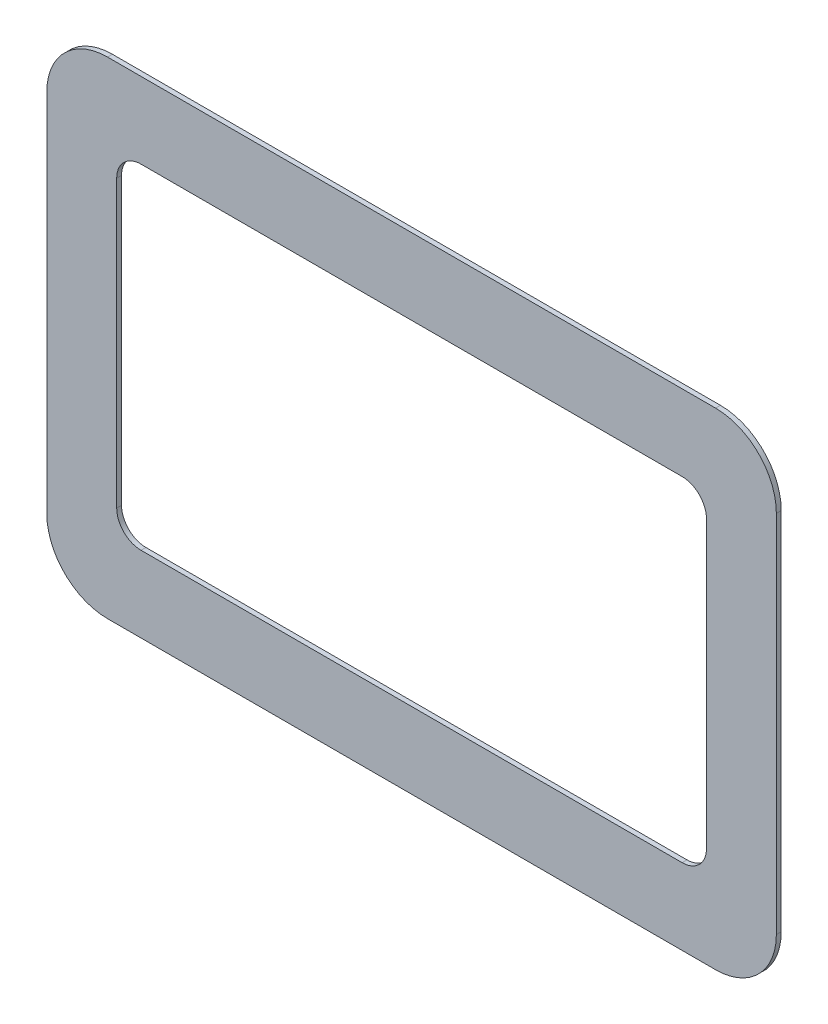
SolidWorks part; units mm, degrees
material "ABS"
ref_plane "Front Plane" through (0, 0, 0) normal (0, 0, 1) x (1, 0, 0)
ref_plane "Top Plane" through (0, 0, 0) normal (0, 1, 0) x (1, 0, 0)
ref_plane "Right Plane" through (0, 0, 0) normal (1, 0, 0) x (0, 0, -1)
sketch "Sketch1" plane through (0, 0, 0) normal (0, 0, 1) x (1, 0, 0)
  line L0 (-151.096, 0) -> (165.8124, 0) construction
  line L1 (0, -100.7307) -> (0, 98.9546) construction
  line L3 (-210.2936, -194.6079) -> (289.7064, -194.6079)
  line L4 (-260.2936, -144.6079) -> (-260.2936, 155.3921)
  line L5 (-210.2936, 205.3921) -> (289.7064, 205.3921)
  line L6 (339.7064, -144.6079) -> (339.7064, 155.3921)
  line L7 (-260.2936, -194.6079) -> (339.7064, 205.3921) construction
  line L8 (-260.2936, 205.3921) -> (339.7064, -194.6079) construction
  arc A0 (289.7064, -194.6079) -> (339.7064, -144.6079) centre (289.7064, -144.6079) ccw
  arc A1 (-210.2936, -194.6079) -> (-260.2936, -144.6079) centre (-210.2936, -144.6079) cw
  arc A2 (289.7064, 205.3921) -> (339.7064, 155.3921) centre (289.7064, 155.3921) cw
  arc A3 (-260.2936, 155.3921) -> (-210.2936, 205.3921) centre (-210.2936, 155.3921) cw
  dimension "D1" = 50
  dimension "D2" = 600
  dimension "D3" = 400
extrude "Boss-Extrude1" add sketch "Sketch1" along normal blind 4
sketch "Sketch3" plane through (0, 0, 4) normal (0, 0, 1) x (1, 0, 0)
  line L0 (39.7064, 305.4843) -> (39.7064, -330.1727) construction
  line L1 (-182.7936, -132.1079) -> (262.2064, -132.1079)
  line L2 (-202.7936, -112.1079) -> (-202.7936, 122.8921)
  line L3 (-182.7936, 142.8921) -> (262.2064, 142.8921)
  line L4 (282.2064, -112.1079) -> (282.2064, 122.8921)
  line L5 (-202.7936, -132.1079) -> (282.2064, 142.8921) construction
  line L6 (-202.7936, 142.8921) -> (282.2064, -132.1079) construction
  line L9 (-260.2936, 5.3921) -> (339.7064, 5.3921) construction
  line L10 (-260.2936, 155.3921) -> (-260.2936, -144.6079) construction
  line L11 (339.7064, -144.6079) -> (339.7064, 155.3921) construction
  arc A0 (262.2064, -132.1079) -> (282.2064, -112.1079) centre (262.2064, -112.1079) ccw
  arc A1 (-182.7936, -132.1079) -> (-202.7936, -112.1079) centre (-182.7936, -112.1079) cw
  arc A2 (262.2064, 142.8921) -> (282.2064, 122.8921) centre (262.2064, 122.8921) cw
  arc A3 (-202.7936, 122.8921) -> (-182.7936, 142.8921) centre (-182.7936, 122.8921) cw
  point P0 (39.7064, 5.3921)
  dimension "D3" = 20
  dimension "D1" = 485
  dimension "D2" = 275
extrude "Cut-Extrude4" cut sketch "Sketch3" against normal blind 4
